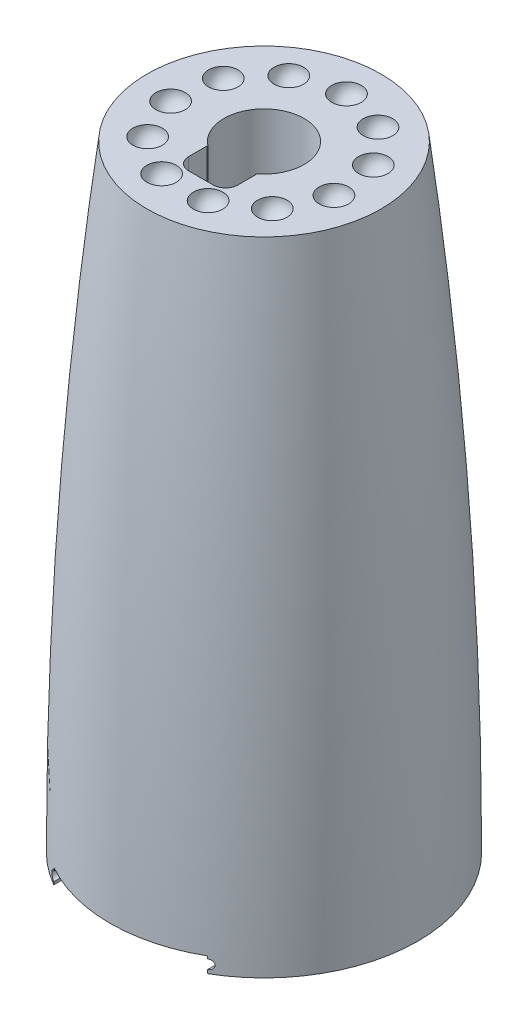
SolidWorks part; units mm, degrees
ref_plane "Alzado" through (0, 0, 0) normal (0, 0, 1) x (1, 0, 0)
ref_plane "Planta" through (0, 0, 0) normal (0, 1, 0) x (1, 0, 0)
ref_plane "Vista lateral" through (0, 0, 0) normal (1, 0, 0) x (0, 0, -1)
sketch "Croquis2" plane through (0, 0, 0) normal (0, 0, 1) x (1, 0, 0)
  line L0 (-13, 140) -> (-13, 200)
  line L1 (-13, 200) -> (-38, 200)
  line L2 (-50, 200) -> (-50, 0) construction
  line L3 (-50, 0) -> (0, 0)
  line L4 (0, 0) -> (0, 140) construction
  line L5 (0, 140) -> (-13, 140)
  line L6 (0, 0) -> (0, 140)
  arc A0 (-50, 0) -> (-38, 200) centre (1622.6667, 0) cw
  dimension "D1" = 200
  dimension "D2" = 60
  dimension "D3" = 50
  dimension "D4" = 13
  dimension "D5" = 25
revolve "Revolución1" add sketch "Croquis2" angle 360 about L4
sketch "Croquis3" plane through (0, 200, 0) normal (0, 1, 0) x (1, 0, 0)
  line L0 (0, 31.6) -> (0, 22)
  line L1 (0, 18) -> (0, 8.4) construction
  line L2 (0, 18) -> (0, 22) construction
  line L3 (0, 2) -> (0, 38) construction
  line L4 (0, 2) -> (0, 13) construction
  arc A0 (0, 22) -> (0, 31.6) centre (0, 26.8) ccw
  arc A1 (0, 8.4) -> (0, 18) centre (0, 13.2) ccw construction
  circle A3 centre (0, 0) radius 38 construction
  circle A7 centre (0, 0) radius 13 construction
  point P3 (0, 20)
  point P7 (0, 38)
  point P16 (0, 20)
  dimension "D1" = 4.8
  dimension "D3" = 20
  dimension "D2" = 2
revolve "Cortar-Revolución1" cut sketch "Croquis3" angle 360 about L0
pattern_circular "MatrizC1" count 11 over 360 about axis through (0, 0, 0) along (0, 1, 0) of "Cortar-Revolución1"
sketch "Croquis6" plane through (0, 200, 0) normal (0, 1, 0) x (1, 0, 0)
  line L1 (8, -10.5) -> (-8, -10.5)
  line L2 (8, -10.5) -> (8, -16.5)
  line L3 (4, -20.5) -> (-4, -20.5)
  line L4 (-8, -10.5) -> (-8, -16.5)
  circle A0 centre (0, 0) radius 13 construction
  circle A1 centre (0, 0) radius 13 construction
  arc A2 (8, -16.5) -> (4, -20.5) centre (4, -16.5) cw
  arc A3 (-4, -20.5) -> (-8, -16.5) centre (-4, -16.5) cw
  point P0 (0, -13)
  point P13 (8, -20.5)
  point P16 (-8, -20.5)
  dimension "D4" = 4
  dimension "D1" = 10
  dimension "D2" = 16
  dimension "D3" = 2.5
sketch "Croquis4" plane through (0, 0, 0) normal (0, -1, 0) x (1, 0, 0)
  line L1 (-25, -25) -> (25, -25)
  line L2 (-25, -25) -> (-25, 25)
  line L3 (-25, 25) -> (25, 25)
  line L4 (25, -25) -> (25, 25)
  line L5 (-25, -25) -> (25, 25) construction
  line L6 (-25, 25) -> (25, -25) construction
  point P0 (0, 0)
  dimension "D1" = 50
extrude "Cortar-Extruir1" cut sketch "Croquis4" against normal blind 100
ref_plane "Plano1" through (0, 0, 125) normal (0, 0, 1) x (1, 0, 0)
sketch "Croquis5" plane through (0, 0, 125) normal (0, 0, 1) x (1, 0, 0)
  line L0 (-25, 3.8593) -> (-25, 5)
  line L1 (-25, 0) -> (25, 0) construction
  line L2 (-25, 0) -> (25, 0)
  line L3 (25, 4.1668) -> (25, 5)
  line L4 (25, 0) -> (-25, 0)
  line L5 (25, 0) -> (25, 1.1668)
  line L6 (25, 5) -> (-25, 5)
  line L7 (-25, 0) -> (-25, 0.8593)
  arc A0 (-25, 3.8593) -> (-25, 0.8593) centre (-25, 2.3593) ccw
  arc A1 (25, 1.1668) -> (25, 4.1668) centre (25, 2.6668) ccw
  point P8 (0, 0)
  point P11 (0, 0)
  point P12 (-25, 0.8728)
  point P13 (0, 0)
  point P14 (25, 21.5642)
  point P15 (25, 1.3453)
  point P16 (0, 0)
  point P17 (0, 0)
  dimension "D2" = 3
  dimension "D3" = 3
  dimension "D1" = 5
extrude "Cortar-Extruir2" cut sketch "Croquis5" against normal up to surface (150 mm away) contours L5 A1 L3 L6 L0 A0 L7 L2 up to face at (0, 50, -25)
extrude "Cortar-Extruir3" cut sketch "Croquis6" against normal up to surface (100 mm away) up to face at (0, 100, 0)
